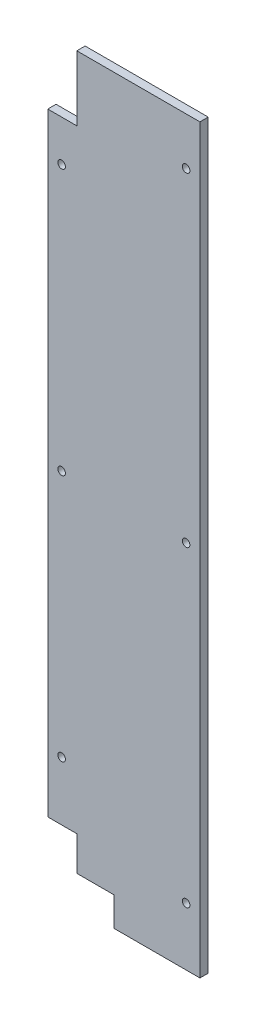
SolidWorks part; units mm, degrees
ref_plane "Front Plane" through (0, 0, 0) normal (0, 0, 1) x (1, 0, 0)
ref_plane "Top Plane" through (0, 0, 0) normal (0, 1, 0) x (1, 0, 0)
ref_plane "Right Plane" through (0, 0, 0) normal (1, 0, 0) x (0, 0, -1)
sketch "Sketch1" plane through (0, 0, 0) normal (0, 0, 1) x (1, 0, 0)
  line L0 (-82.419, -326.8557) -> (-82.419, -305.8557)
  line L1 (-109.419, 209.1443) -> (-20.419, 209.1443)
  line L2 (-130.419, 162.1753) -> (-130.419, -281.0269)
  line L3 (-82.419, -326.8557) -> (-20.419, -326.8557)
  line L4 (-20.419, 209.1443) -> (-20.419, -326.8557)
  line L5 (-82.419, -305.8557) -> (-109.419, -305.8557)
  line L7 (-109.419, 162.1753) -> (-109.419, 209.1443)
  line L8 (-130.419, -281.0269) -> (-109.419, -281.0269)
  line L9 (-109.419, -281.0269) -> (-109.419, -305.8557)
  line L10 (-130.419, 162.1753) -> (-109.419, 162.1753)
  point P12 (-83.0598, -326.8557)
  dimension "D1" = 536
  dimension "D2" = 110
  dimension "D4" = 21
  dimension "D5" = 21
  dimension "D6" = 21
  dimension "D7" = 48
extrude "Boss-Extrude1" add sketch "Sketch1" along normal blind 6 contours L1 L4 L3 L0 L5 L9 L8 L2 L10 L7
sketch "Sketch2" plane through (0, 0, 6) normal (0, 0, 1) x (1, 0, 0)
  line L0 (-130.419, 162.1753) -> (-130.419, -281.0269) construction
  line L1 (-20.419, 209.1443) -> (-20.419, -326.8557) construction
  circle A0 centre (-120.419, -59.4258) radius 2.75
  circle A1 centre (-30.419, -59.4258) radius 2.75
  circle A2 centre (-30.419, 174.9442) radius 2.75
  circle A3 centre (-30.419, -284.9376) radius 2.75
  circle A4 centre (-120.419, -238.5628) radius 2.75
  circle A5 centre (-120.419, 132.4555) radius 2.75
  point P12 (0, 0)
  point P17 (0, 0)
  dimension "D1" = 5.5
  dimension "D2" = 10
  dimension "D3" = 10
extrude "Cut-Extrude1" cut sketch "Sketch2" against normal blind 10
